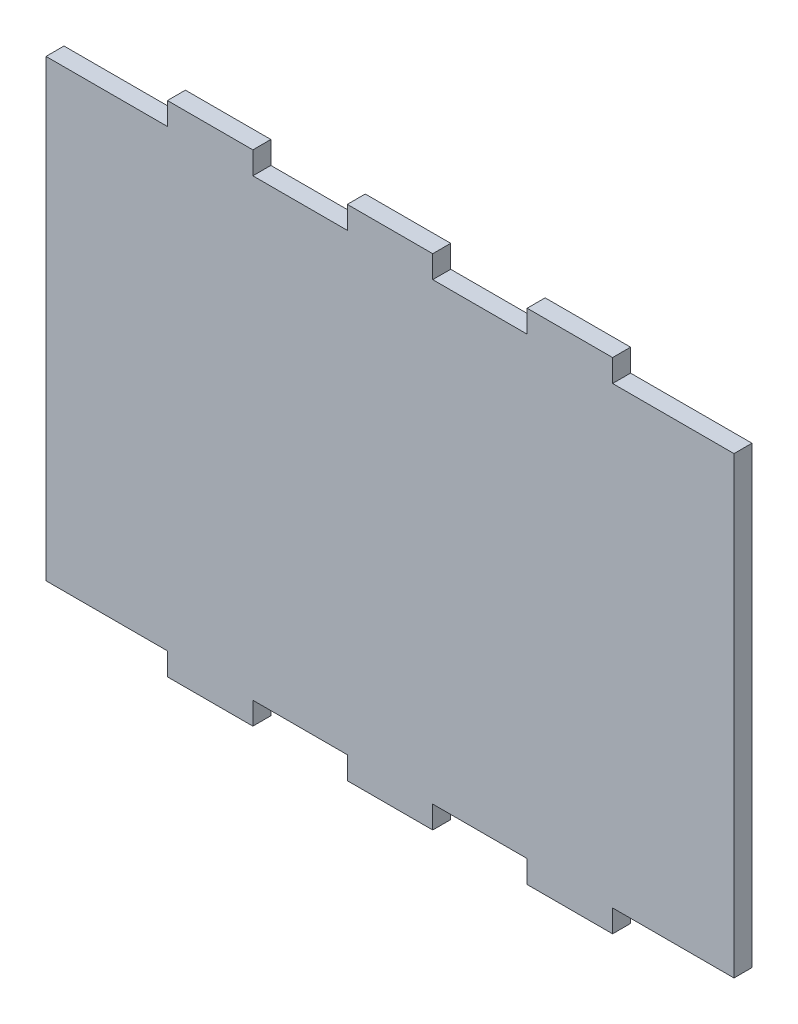
SolidWorks part; units mm, degrees
ref_plane "Plan de face" through (0, 0, 0) normal (0, 0, 1) x (1, 0, 0)
ref_plane "Plan de dessus" through (0, 0, 0) normal (0, 1, 0) x (1, 0, 0)
ref_plane "Plan de droite" through (0, 0, 0) normal (1, 0, 0) x (0, 0, -1)
sketch "Esquisse1" plane through (0, 0, 0) normal (0, 0, 1) x (1, 0, 0)
  line L0 (-15.25, 25.25) -> (-4.75, 25.25)
  line L1 (-38.25, 25.25) -> (-24.75, 25.25)
  line L2 (-38.25, 25.25) -> (-38.25, -25.25)
  line L3 (-38.25, -25.25) -> (-24.75, -25.25)
  line L4 (38.25, 25.25) -> (38.25, -25.25)
  line L5 (-38.25, 25.25) -> (38.25, -25.25) construction
  line L6 (-38.25, -25.25) -> (38.25, 25.25) construction
  line L8 (-24.75, 25.25) -> (-24.75, 27.75)
  line L9 (-24.75, 27.75) -> (-15.25, 27.75)
  line L10 (-15.25, 25.25) -> (-15.25, 27.75)
  line L12 (4.75, 25.25) -> (4.75, 27.75)
  line L13 (4.75, 27.75) -> (-4.75, 27.75)
  line L14 (-4.75, 25.25) -> (-4.75, 27.75)
  line L16 (15.25, 25.25) -> (15.25, 27.75)
  line L17 (15.25, 27.75) -> (24.75, 27.75)
  line L18 (24.75, 25.25) -> (24.75, 27.75)
  line L20 (-24.75, -25.25) -> (-24.75, -27.75)
  line L21 (-24.75, -27.75) -> (-15.25, -27.75)
  line L22 (-15.25, -25.25) -> (-15.25, -27.75)
  line L24 (-4.75, -25.25) -> (-4.75, -27.75)
  line L25 (-4.75, -27.75) -> (4.75, -27.75)
  line L26 (4.75, -25.25) -> (4.75, -27.75)
  line L28 (15.25, -25.25) -> (15.25, -27.75)
  line L29 (15.25, -27.75) -> (24.75, -27.75)
  line L30 (24.75, -25.25) -> (24.75, -27.75)
  line L31 (4.75, 25.25) -> (15.25, 25.25)
  line L32 (24.75, 25.25) -> (38.25, 25.25)
  line L33 (-15.25, -25.25) -> (-4.75, -25.25)
  line L34 (4.75, -25.25) -> (15.25, -25.25)
  line L35 (24.75, -25.25) -> (38.25, -25.25)
  point P0 (0, 0)
  point P18 (0, 27.75)
  point P19 (-20, 27.75)
  point P22 (20, 27.75)
  dimension "D1" = 50.5
  dimension "D2" = 76.5
  dimension "D3" = 20
  dimension "D4" = 20
  dimension "D5" = 9.5
  dimension "D6" = 2.5
extrude "Boss.-Extru.1" add sketch "Esquisse1" along normal blind 2 contours L2 L3 L20 L21 L22 L33 L24 L25 L26 L34 L28 L29 L30 L35 L4 L32 L18 L17 L16 L31 L12 L13 L14 L0 L10 L9 L8 L1
